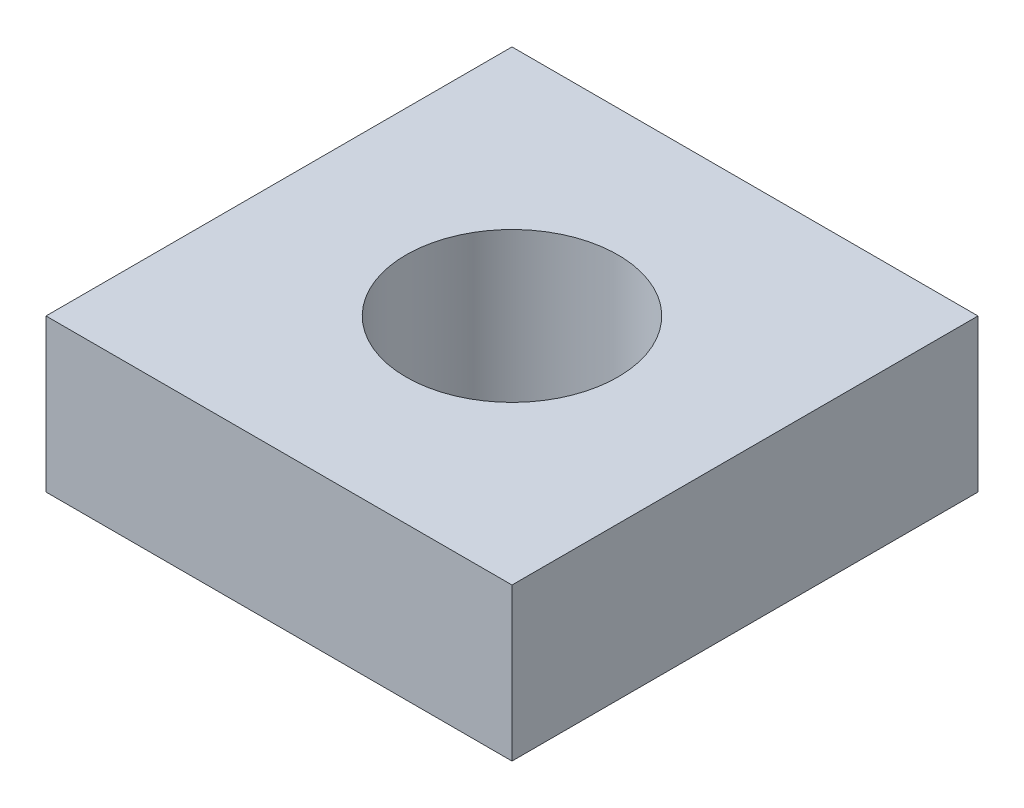
SolidWorks part; units mm, degrees
ref_plane "Front Plane" through (0, 0, 0) normal (0, 0, 1) x (1, 0, 0)
ref_plane "Top Plane" through (0, 0, 0) normal (0, 1, 0) x (1, 0, 0)
ref_plane "Right Plane" through (0, 0, 0) normal (1, 0, 0) x (0, 0, -1)
sketch "Sketch1" plane through (0, 0, 0) normal (0, 1, 0) x (1, 0, 0)
  line L1 (2.75, 2.75) -> (-2.75, 2.75)
  line L2 (2.75, 2.75) -> (2.75, -2.75)
  line L3 (2.75, -2.75) -> (-2.75, -2.75)
  line L4 (-2.75, 2.75) -> (-2.75, -2.75)
  line L5 (2.75, 2.75) -> (-2.75, -2.75) construction
  line L6 (2.75, -2.75) -> (-2.75, 2.75) construction
  point P0 (0, 0)
  dimension "D1" = 5.5
  dimension "D2" = 5.5
extrude "Boss-Extrude1" add sketch "Sketch1" along normal blind 1.8
hole_wizard "M3x0.5 Tapped Hole1" positions "Sketch2" profile "Sketch3" tap size "M3x0.5" standard "ANSI Metric" end condition through all
sketch "Sketch2" plane through (0, 1.8, 0) normal (0, 1, 0) x (1, 0, 0)
  point P0 (0, 0)
cosmetic thread "Hole Thread1"
sketch "Sketch3" plane through (0, 1.8, 0) normal (1, 0, 0) x (0, 0, 1)
  line L0 (0, 0) -> (0, 1.8)
  line L1 (0, 1.8) -> (1.25, 1.8)
  line L2 (1.25, 1.8) -> (1.25, 0)
  line L5 (1.25, 0) -> (0, 0)
  line L11 (0, -6.35) -> (0, 107.95) construction
  dimension "Thru Tap Drill Dia." = 2.5
  dimension "Thru Tap Drill Depth" = 1.8
